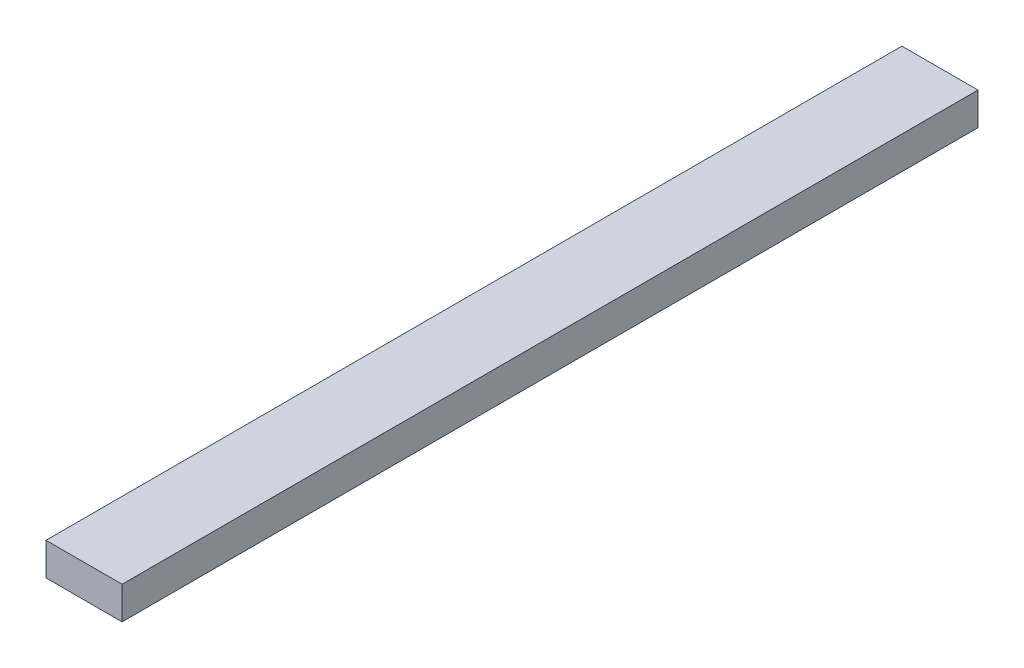
SolidWorks part; units mm, degrees
material "Pine"
ref_plane "Front Plane" through (0, 0, 0) normal (0, 0, 1) x (1, 0, 0)
ref_plane "Top Plane" through (0, 0, 0) normal (0, 1, 0) x (1, 0, 0)
ref_plane "Right Plane" through (0, 0, 0) normal (1, 0, 0) x (0, 0, -1)
sketch "Sketch1" plane through (0, 0, 0) normal (0, 0, 1) x (1, 0, 0)
  line L1 (-44.45, -19.05) -> (44.45, -19.05)
  line L2 (-44.45, -19.05) -> (-44.45, 19.05)
  line L3 (-44.45, 19.05) -> (44.45, 19.05)
  line L4 (44.45, -19.05) -> (44.45, 19.05)
  line L5 (-44.45, -19.05) -> (44.45, 19.05) construction
  line L6 (-44.45, 19.05) -> (44.45, -19.05) construction
  point P0 (0, 0)
  dimension "D1" = 88.9
  dimension "D2" = 38.1
extrude "Boss-Extrude1" add sketch "Sketch1" along normal blind 1000
